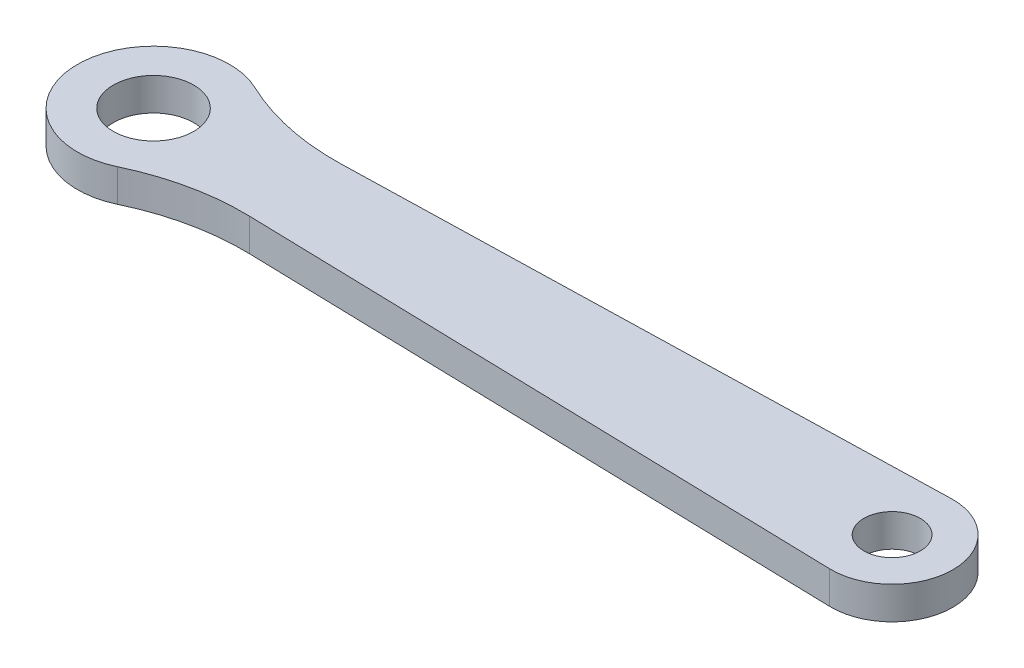
SolidWorks part; units mm, degrees
ref_plane "前视基准面" through (0, 0, 0) normal (0, 0, 1) x (1, 0, 0)
ref_plane "上视基准面" through (0, 0, 0) normal (0, 1, 0) x (1, 0, 0)
ref_plane "右视基准面" through (0, 0, 0) normal (1, 0, 0) x (0, 0, -1)
sketch "草图1" plane through (0, 0, 0) normal (0, 1, 0) x (1, 0, 0)
  line L0 (0, 0) -> (167.3119, 0) construction
  line L1 (65.1964, 20.9385) -> (339.2798, 27.9907)
  line L2 (65.1964, -20.9385) -> (339.2798, -27.9907)
  circle A0 centre (0, 0) radius 18.5
  circle A1 centre (0, 0) radius 35 construction
  arc A3 (15.0541, 31.5971) -> (15.0541, -31.5971) centre (0, 0) ccw
  circle A4 centre (340, 0) radius 13
  circle A5 centre (340, 0) radius 28 construction
  arc A6 (339.2798, 27.9907) -> (339.2798, -27.9907) centre (340, 0) cw
  arc A7 (15.0541, 31.5971) -> (65.1964, 20.9385) centre (62.367, 130.9021) ccw
  arc A8 (15.0541, -31.5971) -> (65.1964, -20.9385) centre (62.367, -130.9021) cw
  point P4 (28.7228, 20)
  point P19 (28.7228, 20)
  dimension "D1" = 37
  dimension "D3" = 70
  dimension "D4" = 26
  dimension "D6" = 56
  dimension "D7" = 110
  dimension "D2" = 20
  dimension "D5" = 340
extrude "凸台-拉伸1" add sketch "草图1" along normal blind 15
